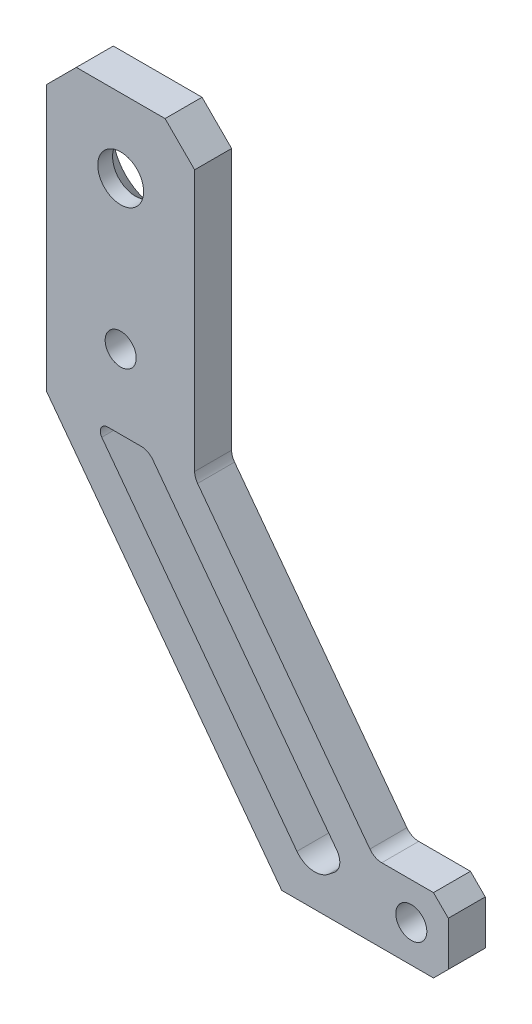
SolidWorks part; units mm, degrees
ref_plane "前视基准面" through (0, 0, 0) normal (0, 0, 1) x (1, 0, 0)
ref_plane "上视基准面" through (0, 0, 0) normal (0, 1, 0) x (1, 0, 0)
ref_plane "右视基准面" through (0, 0, 0) normal (1, 0, 0) x (0, 0, -1)
sketch "草图1" plane through (0, 0, 0) normal (0, 0, 1) x (1, 0, 0)
  line L0 (-10, 10) -> (-10, -30)
  line L1 (-10, -30) -> (21.7769, -72.5)
  line L2 (21.7769, -72.5) -> (44.3, -72.5)
  line L3 (44.3, -72.5) -> (44.3, -62.5)
  line L4 (44.3, -62.5) -> (34.3, -62.5)
  line L5 (34.3, -62.5) -> (10, -30)
  line L6 (10, -30) -> (10, 10)
  line L7 (10, 10) -> (-10, 10)
  line L8 (-3.7569, -30) -> (3.7569, -30)
  line L9 (25.6861, -69.3785) -> (30.3909, -65.6215)
  line L10 (-3.7569, -30) -> (25.6861, -69.3785)
  line L11 (30.3909, -65.6215) -> (3.7569, -30)
  line L12 (30.2956, -65.4941) -> (5.9956, -32.9941) construction
  line L13 (-5.9956, -27.0059) -> (25.7814, -69.5059) construction
  circle A0 centre (39.3, -67.5) radius 2.1
  circle A1 centre (0, 0) radius 3.1
  point P10 (0, 10)
  dimension "D1" = 4.2
  dimension "D2" = 39.3
  dimension "D3" = 6.2
  dimension "D5" = 10
  dimension "D7" = 5
  dimension "D8" = 5
  dimension "D12" = 67.5
  dimension "D4" = 10
  dimension "D6" = 20
  dimension "D9" = 10
  dimension "D10" = 40
  dimension "D11" = 10
  dimension "D13" = 5
extrude "凸台-拉伸1" add sketch "草图1" along normal mid plane 5
fillet "圆角1" radius 2 4 edges at (34.3, -62.5, 0) (10, -30, 0) (3.7569, -30, 0) (30.3909, -65.6215, 0)
fillet "圆角2" radius 3 1 edges at (25.6861, -69.3785, 0)
chamfer "倒角1" distance 4 angle 45 2 edges at (10, 10, 0) (-10, 10, 0)
chamfer "倒角2" distance 2 angle 45 2 edges at (44.3, -72.5, 0) (44.3, -62.5, 0)
fillet "圆角3" radius 1 1 edges at (-3.7569, -30, 0)
sketch "草图2" plane through (0, 0, 2.5) normal (0, 0, 1) x (1, 0, 0)
  circle A0 centre (0, -20) radius 2.1
  circle A1 centre (0, 0) radius 3.1 construction
  dimension "D1" = 4.2
  dimension "D2" = 20
extrude "切除-拉伸1" cut sketch "草图2" against normal blind 5
chamfer "倒角3" distance 3 angle 45 1 edges at (3.1, 0, -2.5)
